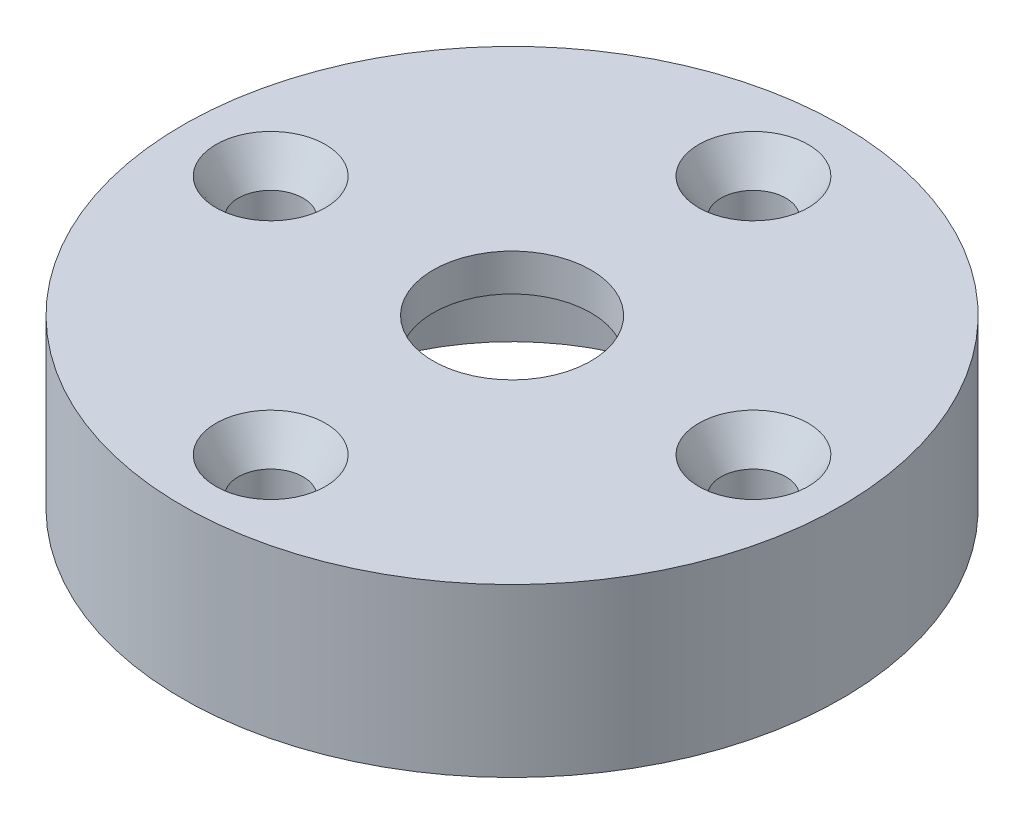
SolidWorks part; units mm, degrees
ref_plane "Front Plane" through (0, 0, 0) normal (0, 0, 1) x (1, 0, 0)
ref_plane "Top Plane" through (0, 0, 0) normal (0, 1, 0) x (1, 0, 0)
ref_plane "Right Plane" through (0, 0, 0) normal (1, 0, 0) x (0, 0, -1)
sketch "Sketch3" plane through (0, 0, 0) normal (0, 0, 1) x (1, 0, 0)
  line L0 (0, 0) -> (0, 34.5832) construction
  line L1 (-11, 0) -> (-17.75, 0)
  line L2 (-17.75, 0) -> (-17.75, 9)
  line L3 (-17.75, 9) -> (-4.25, 9)
  line L4 (-4.25, 9) -> (-4.25, 7)
  line L5 (-4.25, 7) -> (-11, 7)
  line L6 (-11, 7) -> (-11, 0)
  point P5 (0, 0)
  dimension "D1" = 35.5
  dimension "D2" = 7
  dimension "D3" = 22
  dimension "D4" = 8.5
  dimension "D5" = 2
revolve "Revolve1" add sketch "Sketch3" angle 360 about L0
sketch "Sketch4" plane through (0, 9, 0) normal (0, 1, 0) x (1, 0, 0)
  circle A0 centre (0, 0) radius 13 construction
  circle A1 centre (0, 13) radius 1.75
  circle A2 centre (13, 0) radius 1.75
  circle A3 centre (0, -13) radius 1.75
  circle A4 centre (-13, 0) radius 1.75
  point P5 (-13, 0)
  point P14 (0, 0)
  dimension "D1" = 26
  dimension "D2" = 3.5
  dimension "D3" = 4
extrude "Cut-Extrude1" cut sketch "Sketch4" against normal up to surface (9 mm away) up to face at (0, 0, -11)
chamfer "Chamfer1" distance 1.2 distance2 1.9 4 edges at (0, 9, 14.75) (13, 9, 1.75) (0, 9, -11.25) (-13, 9, 1.75)
